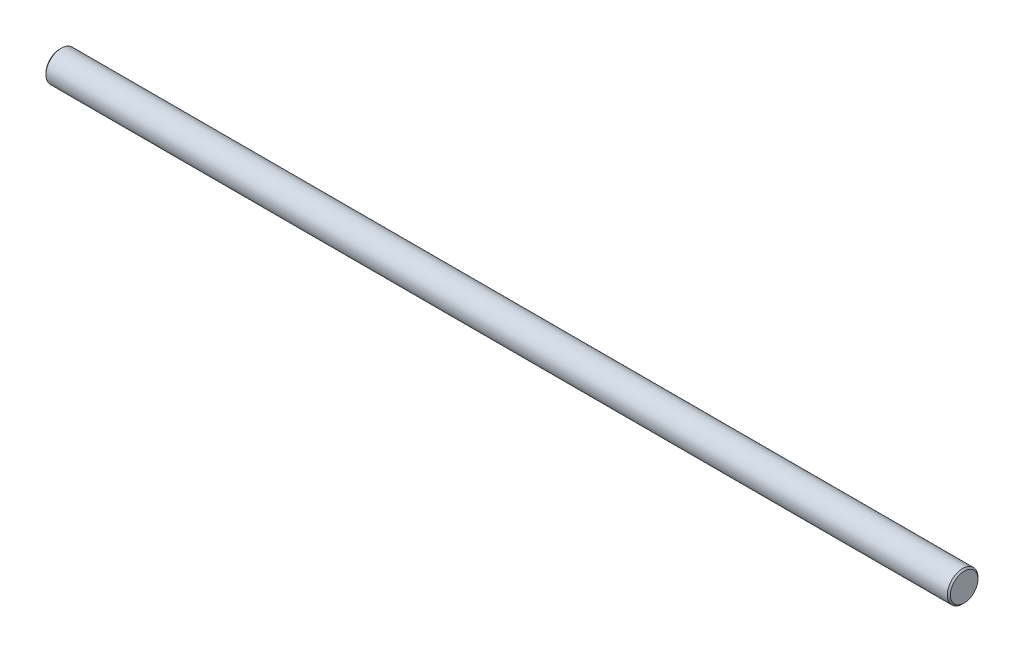
SolidWorks part; units mm, degrees
material "5052-H32"
ref_plane "Front Plane" through (0, 0, 0) normal (0, 0, 1) x (1, 0, 0)
ref_plane "Top Plane" through (0, 0, 0) normal (0, 1, 0) x (1, 0, 0)
ref_plane "Right Plane" through (0, 0, 0) normal (1, 0, 0) x (0, 0, -1)
ref_plane "Plane1" through (-88.4, 26.8026, 0) normal (1, 0, 0) x (0, 0, -1)
sketch "Sketch2" plane through (0, 0, 0) normal (1, 0, 0) x (0, 0, -1)
  circle A0 centre (0, 10.5734) radius 3 construction
  circle A1 centre (0, 10.5734) radius 3
extrude "Boss-Extrude1" add sketch "Sketch2" against normal up to vertex (88.4 mm away)
chamfer "Chamfer1" distance 0.3 angle 45 1 edges at (0, 10.5734, -3)
mirror "Mirror1" about plane through (-88.4, 10.5734, 0) normal (1, 0, 0) of "Chamfer1", "Boss-Extrude1"
